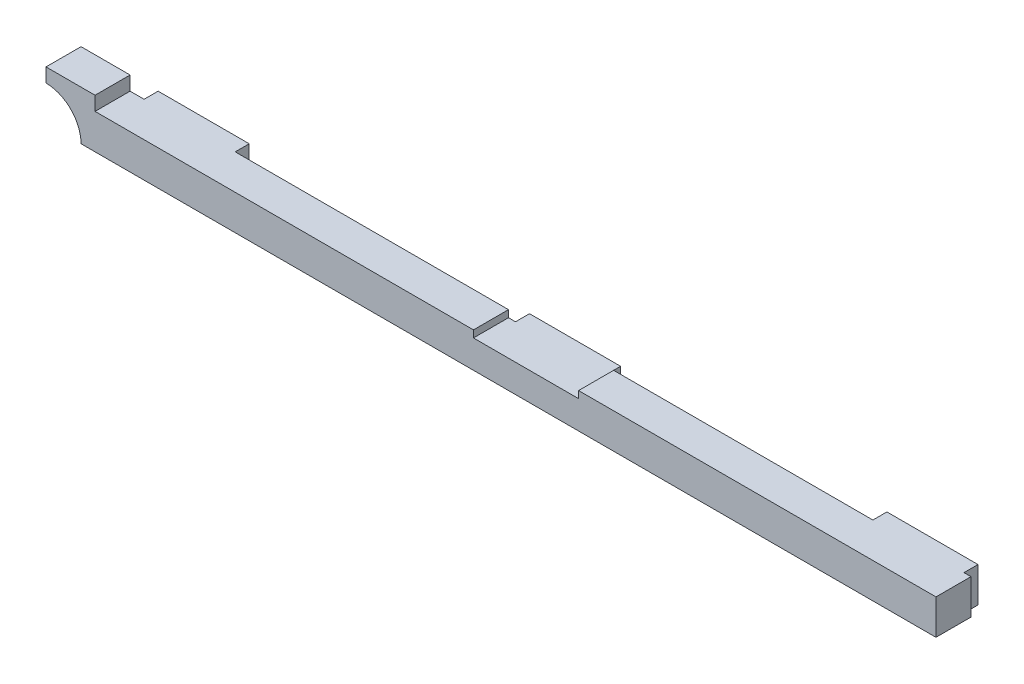
SolidWorks part; units mm, degrees
ref_plane "Plan de face" through (0, 0, 0) normal (0, 0, 1) x (1, 0, 0)
ref_plane "Plan de dessus" through (0, 0, 0) normal (0, 1, 0) x (1, 0, 0)
ref_plane "Plan de droite" through (0, 0, 0) normal (1, 0, 0) x (0, 0, -1)
sketch "Base pièce" plane through (0, 0, 0) normal (0, 0, 1) x (1, 0, 0)
  line L0 (0, 0) -> (15, 0)
  line L1 (15, 0) -> (15, 1)
  line L2 (15, 1) -> (66, 1)
  line L3 (66, 1) -> (66, -4)
  line L4 (66, -4) -> (-56, -4)
  line L5 (0, 0) -> (0, 1)
  line L6 (0, 1) -> (-54, 1)
  line L7 (-54, 1) -> (-54, 3)
  line L8 (-54, 3) -> (-61, 3)
  line L9 (-61, 3) -> (-61, 1)
  arc A0 (-56, -4) -> (-61, 1) centre (-61, -4) ccw
  dimension "D8" = 5
  dimension "D1" = 1
  dimension "D2" = 1
  dimension "D3" = 15
  dimension "D4" = 5
  dimension "D5" = 2
  dimension "D6" = 2
  dimension "D7" = 7
  dimension "D9" = 51
  dimension "D10" = 54
extrude "Boss.-Extru.1" add sketch "Base pièce" along normal blind 5 contours L4 A0 L9 L8 L7 L6 L5 L0 L1 L2 L3
sketch "Trou 1" plane through (0, 3, 0) normal (0, 1, 0) x (1, 0, 0)
  line L0 (-61, -5) -> (-61, 0) construction
  line L1 (-54, -5) -> (-61, -5) construction
  circle A0 centre (-59.5, -2.5) radius 0.5
  dimension "D2" = 1
  dimension "D1" = 1.5
  dimension "D3" = 2.5
sketch "Autres trous" plane through (0, 1, 0) normal (0, 1, 0) x (1, 0, 0)
  line L0 (-61, -5) -> (-61, 0) construction
  line L1 (0, -5) -> (-54, -5) construction
  line L2 (15, -5) -> (66, -5) construction
  circle A0 centre (-37.5, -2.5) radius 0.5
  circle A1 centre (-19, -2.5) radius 0.5
  circle A2 centre (-6.5, -2.5) radius 0.5
  circle A3 centre (21.5, -2.5) radius 0.5
  circle A4 centre (35, -2.5) radius 0.5
  point P16 (-61, -2.5)
  dimension "D1" = 1
  dimension "D4" = 1
  dimension "D7" = 1
  dimension "D10" = 1
  dimension "D11" = 1
  dimension "D2" = 23.5
  dimension "D3" = 2.5
  dimension "D5" = 2.5
  dimension "D6" = 42
  dimension "D8" = 2.5
  dimension "D9" = 54.5
  dimension "D12" = 2.5
  dimension "D13" = 2.5
  dimension "D14" = 82.5
  dimension "D15" = 96
sketch "Esquisse1" plane through (0, 0, 0) normal (0, 0, -1) x (-1, 0, 0)
  line L0 (-15, 1) -> (-66, 1) construction
  line L1 (-65, 1) -> (-52, 1)
  line L2 (-65, 1) -> (-65, -4)
  line L3 (-65, -4) -> (-52, -4)
  line L4 (-52, 1) -> (-52, -4)
  line L5 (-66, -4) -> (56, -4) construction
  line L6 (0, 0) -> (-15, 0) construction
  line L7 (-14, 0) -> (-1, 0)
  line L8 (-14, 0) -> (-14, -4)
  line L9 (-14, -4) -> (-1, -4)
  line L10 (-1, 0) -> (-1, -4)
  line L11 (0, 1) -> (54, 1) construction
  line L12 (39, 1) -> (52, 1)
  line L13 (39, 1) -> (39, -4)
  line L14 (39, -4) -> (52, -4)
  line L15 (52, 1) -> (52, -4)
  line L16 (54, 1) -> (54, 3) construction
  line L17 (-15, 0) -> (-15, 1) construction
  line L18 (-66, 1) -> (-66, -4) construction
  dimension "D1" = 13
  dimension "D2" = 13
  dimension "D3" = 13
  dimension "D4" = 2
  dimension "D5" = 1
  dimension "D6" = 1
extrude "Boss.-Extru.2" add sketch "Esquisse1" along normal blind 2
